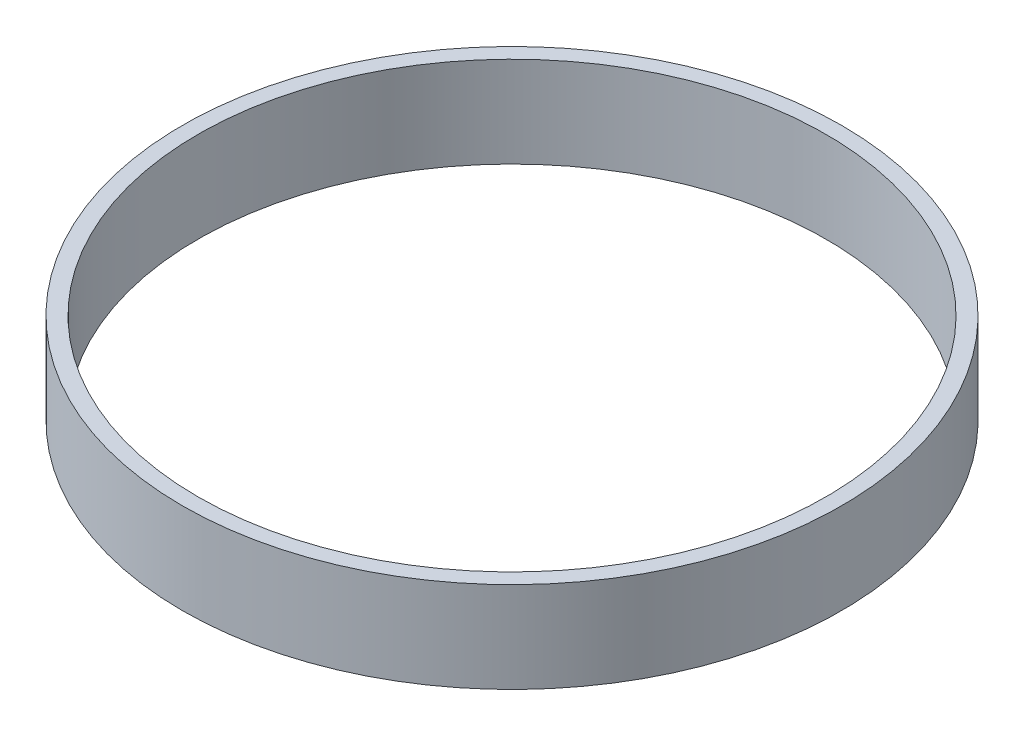
SolidWorks part; units mm, degrees
ref_plane "Front Plane" through (0, 0, 0) normal (0, 0, 1) x (1, 0, 0)
ref_plane "Top Plane" through (0, 0, 0) normal (0, 1, 0) x (1, 0, 0)
ref_plane "Right Plane" through (0, 0, 0) normal (1, 0, 0) x (0, 0, -1)
sketch "Sketch1" plane through (0, 0, 0) normal (0, 1, 0) x (1, 0, 0)
  circle A0 centre (0, 0) radius 24.205
  circle A1 centre (0, 0) radius 25.405
  dimension "D1" = 48.41
  dimension "D2" = 1.2
extrude "Boss-Extrude1" add sketch "Sketch1" along normal blind 7
equation "\"D1@Sketch1\"=1.9in+0.15mm"
